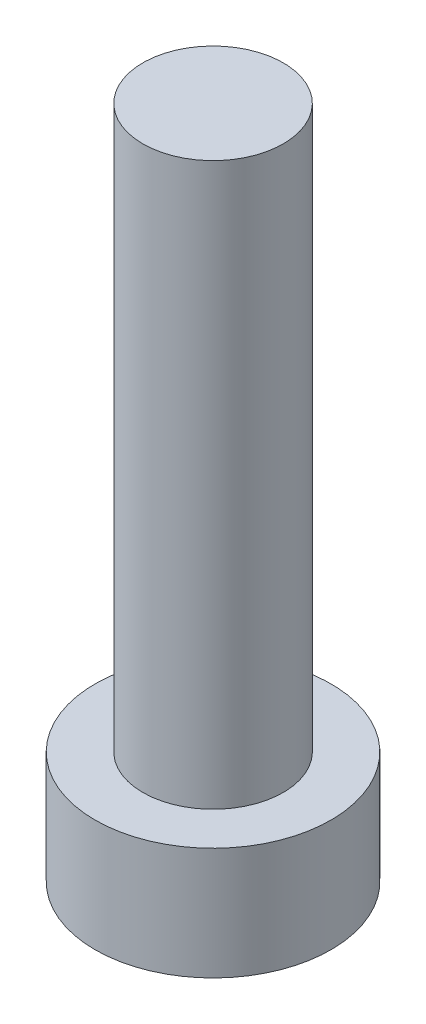
SolidWorks part; units mm, degrees
ref_plane "前视基准面" through (0, 0, 0) normal (0, 0, 1) x (1, 0, 0)
ref_plane "上视基准面" through (0, 0, 0) normal (0, 1, 0) x (1, 0, 0)
ref_plane "右视基准面" through (0, 0, 0) normal (1, 0, 0) x (0, 0, -1)
sketch "草图1" plane through (0, 0, 0) normal (0, 1, 0) x (1, 0, 0)
  circle A0 centre (0, 0) radius 2.1
  dimension "D1" = 4.2
extrude "凸台-拉伸1" add sketch "草图1" along normal blind 2
sketch "草图2" plane through (0, 2, 0) normal (0, 1, 0) x (1, 0, 0)
  circle A0 centre (0, 0) radius 1.25
  dimension "D1" = 2.5
extrude "凸台-拉伸2" add sketch "草图2" along normal blind 10
cosmetic thread "装饰螺纹线1" parameters "D2"=1.5
sketch "草图3" plane through (0, 0, 0) normal (0, -1, 0) x (1, 0, 0)
  line L1 (1, 0) -> (0.5, 0.866)
  line L2 (0.5, 0.866) -> (-0.5, 0.866)
  line L3 (-0.5, 0.866) -> (-1, 0)
  line L4 (-1, 0) -> (-0.5, -0.866)
  line L5 (-0.5, -0.866) -> (0.5, -0.866)
  line L6 (0.5, -0.866) -> (1, 0)
  circle A0 centre (0, 0) radius 0.866 construction
  dimension "D1" = 2
extrude "切除-拉伸1" cut sketch "草图3" against normal blind 1.5
